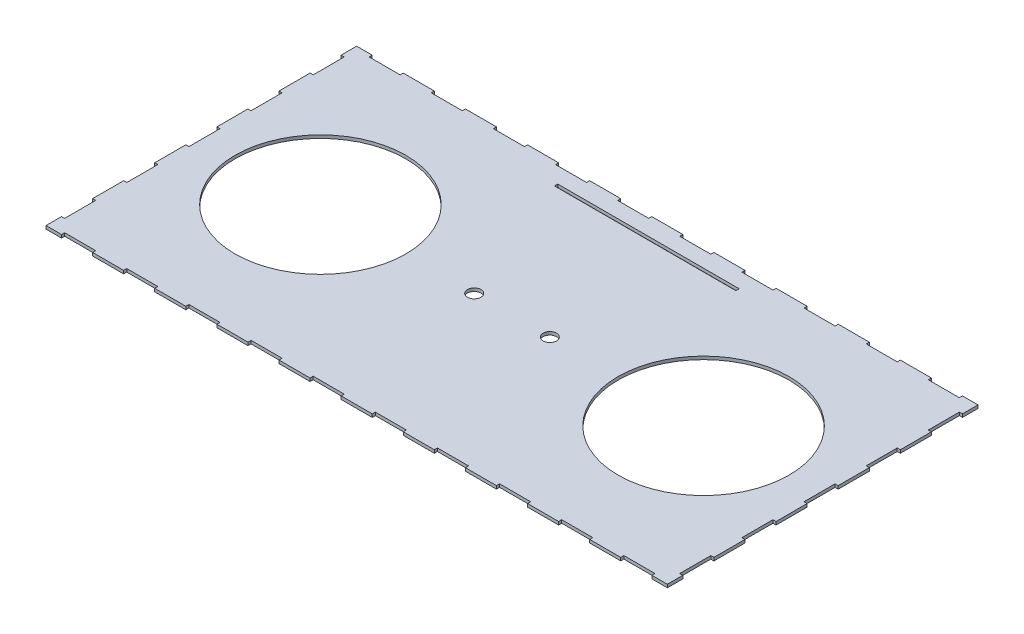
SolidWorks part; units mm, degrees
ref_plane "Front Plane" through (0, 0, 0) normal (0, 0, 1) x (1, 0, 0)
ref_plane "Top Plane" through (0, 0, 0) normal (0, 1, 0) x (1, 0, 0)
ref_plane "Right Plane" through (0, 0, 0) normal (1, 0, 0) x (0, 0, -1)
sketch "Sketch1" plane through (0, 0, 0) normal (0, 1, 0) x (1, 0, 0)
  line L81 (0, 0) -> (600, 0)
  line L82 (0, 0) -> (0, 300)
  line L83 (0, 300) -> (600, 300)
  line L84 (600, 0) -> (600, 300)
  dimension "D1" = 300
  dimension "D2" = 600
extrude "Boss-Extrude1" add sketch "Sketch1" along normal blind 3
sketch "Sketch2" plane through (0, 3, 0) normal (0, 1, 0) x (1, 0, 0)
  line L0 (75, 0) -> (75, 3)
  line L1 (15, 0) -> (45, 0)
  line L2 (15, 0) -> (15, 3)
  line L3 (15, 3) -> (45, 3)
  line L4 (45, 0) -> (45, 3)
  line L5 (75, 0) -> (105, 0)
  line L6 (105, 0) -> (105, 3)
  line L7 (75, 3) -> (105, 3)
  line L8 (135, 0) -> (135, 3)
  line L9 (135, 0) -> (165, 0)
  line L10 (165, 0) -> (165, 3)
  line L11 (135, 3) -> (165, 3)
  line L12 (195, 0) -> (195, 3)
  line L13 (195, 0) -> (225, 0)
  line L14 (225, 0) -> (225, 3)
  line L15 (195, 3) -> (225, 3)
  line L16 (255, 0) -> (255, 3)
  line L17 (255, 0) -> (285, 0)
  line L18 (285, 0) -> (285, 3)
  line L19 (255, 3) -> (285, 3)
  line L20 (315, 0) -> (315, 3)
  line L21 (315, 0) -> (345, 0)
  line L22 (345, 0) -> (345, 3)
  line L23 (315, 3) -> (345, 3)
  line L24 (375, 0) -> (375, 3)
  line L25 (375, 0) -> (405, 0)
  line L26 (405, 0) -> (405, 3)
  line L27 (375, 3) -> (405, 3)
  line L28 (435, 0) -> (435, 3)
  line L29 (435, 0) -> (465, 0)
  line L30 (465, 0) -> (465, 3)
  line L31 (435, 3) -> (465, 3)
  line L32 (495, 0) -> (495, 3)
  line L33 (495, 0) -> (525, 0)
  line L34 (525, 0) -> (525, 3)
  line L35 (495, 3) -> (525, 3)
  line L36 (555, 0) -> (555, 3)
  line L37 (555, 0) -> (585, 0)
  line L38 (585, 0) -> (585, 3)
  line L39 (555, 3) -> (585, 3)
  line L40 (555, 297) -> (585, 297)
  line L41 (0, 150) -> (600, 150) construction
  line L42 (0, 300) -> (0, 0) construction
  line L43 (600, 0) -> (600, 300) construction
  line L44 (585, 300) -> (585, 297)
  line L45 (555, 300) -> (585, 300)
  line L46 (555, 300) -> (555, 297)
  line L47 (495, 297) -> (525, 297)
  line L48 (525, 300) -> (525, 297)
  line L49 (495, 300) -> (525, 300)
  line L50 (495, 300) -> (495, 297)
  line L51 (435, 297) -> (465, 297)
  line L52 (465, 300) -> (465, 297)
  line L53 (435, 300) -> (465, 300)
  line L54 (435, 300) -> (435, 297)
  line L55 (375, 297) -> (405, 297)
  line L56 (405, 300) -> (405, 297)
  line L57 (375, 300) -> (405, 300)
  line L58 (375, 300) -> (375, 297)
  line L59 (315, 297) -> (345, 297)
  line L60 (345, 300) -> (345, 297)
  line L61 (315, 300) -> (345, 300)
  line L62 (315, 300) -> (315, 297)
  line L63 (255, 297) -> (285, 297)
  line L64 (285, 300) -> (285, 297)
  line L65 (255, 300) -> (285, 300)
  line L66 (255, 300) -> (255, 297)
  line L67 (195, 297) -> (225, 297)
  line L68 (225, 300) -> (225, 297)
  line L69 (195, 300) -> (225, 300)
  line L70 (195, 300) -> (195, 297)
  line L71 (135, 297) -> (165, 297)
  line L72 (165, 300) -> (165, 297)
  line L73 (135, 300) -> (165, 300)
  line L74 (135, 300) -> (135, 297)
  line L75 (75, 297) -> (105, 297)
  line L76 (105, 300) -> (105, 297)
  line L77 (75, 300) -> (105, 300)
  line L78 (45, 300) -> (45, 297)
  line L79 (15, 297) -> (45, 297)
  line L80 (15, 300) -> (15, 297)
  line L81 (15, 300) -> (45, 300)
  line L82 (75, 300) -> (75, 297)
  line L83 (0, 0) -> (600, 0) construction
  line L84 (0, 225) -> (0, 195)
  line L85 (0, 285) -> (3, 285)
  line L86 (0, 285) -> (0, 255)
  line L87 (0, 255) -> (3, 255)
  line L88 (3, 285) -> (3, 255)
  line L89 (0, 225) -> (3, 225)
  line L90 (3, 225) -> (3, 195)
  line L91 (0, 195) -> (3, 195)
  line L92 (0, 165) -> (0, 135)
  line L93 (0, 165) -> (3, 165)
  line L94 (3, 165) -> (3, 135)
  line L95 (0, 135) -> (3, 135)
  line L96 (0, 105) -> (0, 75)
  line L97 (0, 105) -> (3, 105)
  line L98 (3, 105) -> (3, 75)
  line L99 (0, 75) -> (3, 75)
  line L100 (0, 45) -> (0, 15)
  line L101 (0, 45) -> (3, 45)
  line L102 (3, 45) -> (3, 15)
  line L103 (0, 15) -> (3, 15)
  line L104 (600, 300) -> (0, 300) construction
  line L105 (300, 300) -> (300, 0) construction
  line L106 (600, 15) -> (597, 15)
  line L107 (597, 45) -> (597, 15)
  line L108 (600, 45) -> (597, 45)
  line L109 (600, 45) -> (600, 15)
  line L110 (600, 75) -> (597, 75)
  line L111 (597, 105) -> (597, 75)
  line L112 (600, 105) -> (597, 105)
  line L113 (600, 105) -> (600, 75)
  line L114 (600, 135) -> (597, 135)
  line L115 (597, 165) -> (597, 135)
  line L116 (600, 165) -> (597, 165)
  line L117 (600, 165) -> (600, 135)
  line L118 (600, 195) -> (597, 195)
  line L119 (597, 225) -> (597, 195)
  line L120 (600, 225) -> (597, 225)
  line L121 (597, 285) -> (597, 255)
  line L122 (600, 255) -> (597, 255)
  line L123 (600, 285) -> (600, 255)
  line L124 (600, 285) -> (597, 285)
  line L125 (600, 225) -> (600, 195)
  circle A0 centre (115, 150) radius 82.5
  circle A1 centre (263.5, 150) radius 6.5
  circle A2 centre (336.5, 150) radius 6.5
  circle A3 centre (485, 150) radius 82.5
  dimension "D10" = 165
  dimension "D12" = 13
  dimension "D1" = 30
  dimension "D2" = 3
  dimension "D4" = 30
  dimension "D5" = 15
  dimension "D6" = 30
  dimension "D7" = 3
  dimension "D9" = 15
  dimension "D11" = 115
  dimension "D13" = 36.5
  dimension "D3" = 10
  dimension "D8" = 5
extrude "Cut-Extrude2" cut sketch "Sketch2" against normal blind 5
sketch "Sketch3" plane through (0, 3, 0) normal (0, 1, 0) x (1, 0, 0)
  line L0 (375, 297) -> (405, 297) construction
  line L1 (212.4, 281.8) -> (387.6, 281.8)
  line L2 (212.4, 281.8) -> (212.4, 278.6)
  line L3 (212.4, 278.6) -> (387.6, 278.6)
  line L4 (387.6, 281.8) -> (387.6, 278.6)
  circle A0 centre (115, 150) radius 82.5 construction
  circle A1 centre (485, 150) radius 82.5 construction
  dimension "D1" = 3.2
  dimension "D2" = 15.2
  dimension "D3" = 97.4
  dimension "D4" = 97.4
extrude "Cut-Extrude3" cut sketch "Sketch3" against normal blind 10
